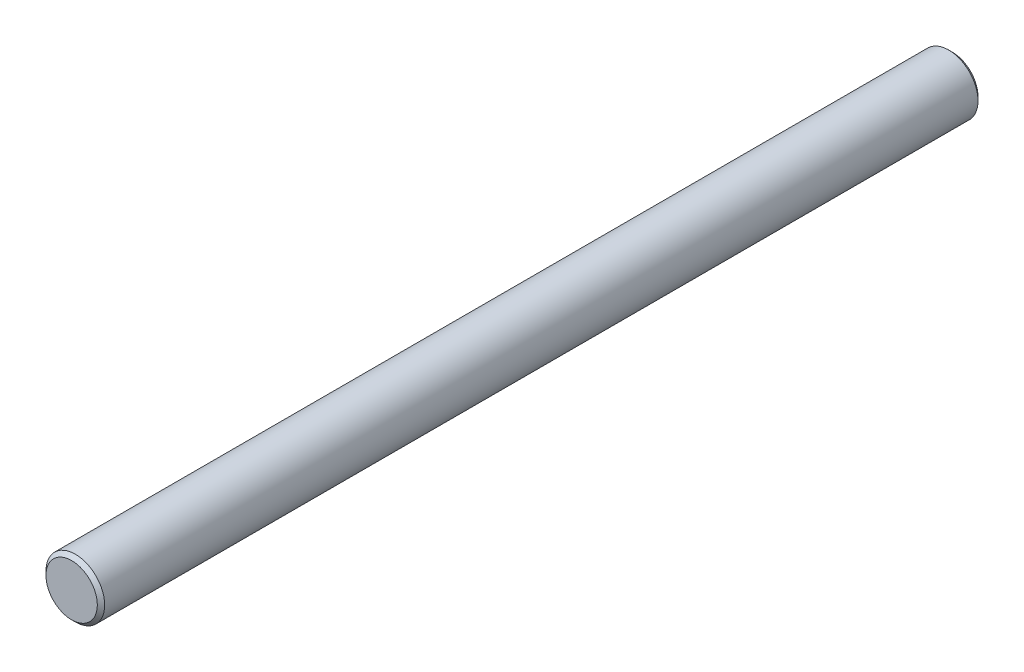
SolidWorks part; units mm, degrees
ref_plane "Ebene vorne" through (0, 0, 0) normal (0, 0, 1) x (1, 0, 0)
ref_plane "Ebene oben" through (0, 0, 0) normal (0, 1, 0) x (1, 0, 0)
ref_plane "Ebene rechts" through (0, 0, 0) normal (1, 0, 0) x (0, 0, -1)
sketch "Skizze1" plane through (0, 0, 0) normal (0, 0, 1) x (1, 0, 0)
  circle A0 centre (0, 0) radius 4
  dimension "D1" = 8
extrude "Aufsatz-Linear austragen1" add sketch "Skizze1" along normal blind 120
chamfer "Fase1" distance 0.5 angle 45 2 edges at (4, 0, 0) (4, 0, 120)
